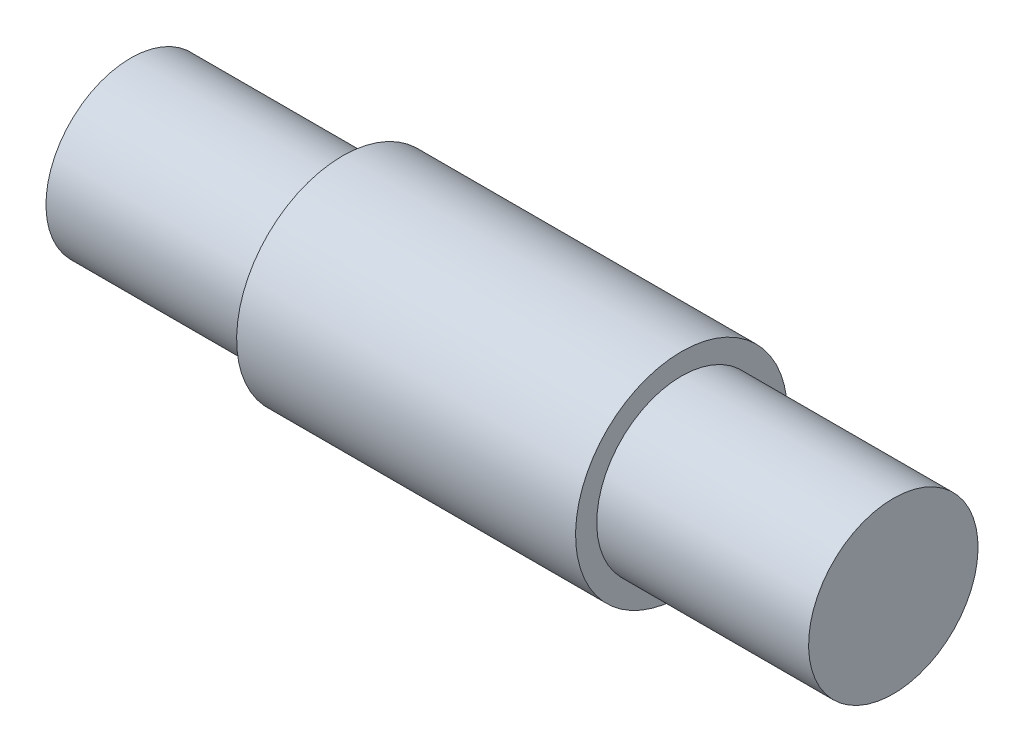
SolidWorks part; units mm, degrees
ref_plane "Front Plane" through (0, 0, 0) normal (0, 0, 1) x (1, 0, 0)
ref_plane "Top Plane" through (0, 0, 0) normal (0, 1, 0) x (1, 0, 0)
ref_plane "Right Plane" through (0, 0, 0) normal (1, 0, 0) x (0, 0, -1)
sketch "Sketch2" plane through (0, 0, 0) normal (0, 0, 1) x (1, 0, 0)
  line L0 (0, 0) -> (4, 0)
  line L1 (4, 0) -> (4, 0.5)
  line L2 (4, 0.5) -> (9, 0.5)
  line L3 (9, 0.5) -> (9, 2.5)
  line L4 (9, 2.5) -> (0, 2.5)
  line L5 (0, 2.5) -> (0, 0)
  dimension "D1" = 4
  dimension "D2" = 5
  dimension "D3" = 0.5
  dimension "D4" = 2
revolve "Revolve1" add sketch "Sketch2" angle 360 about L4
mirror "Mirror1" about plane through (0, 2.5, 0) normal (1, 0, 0) of "Revolve1"
